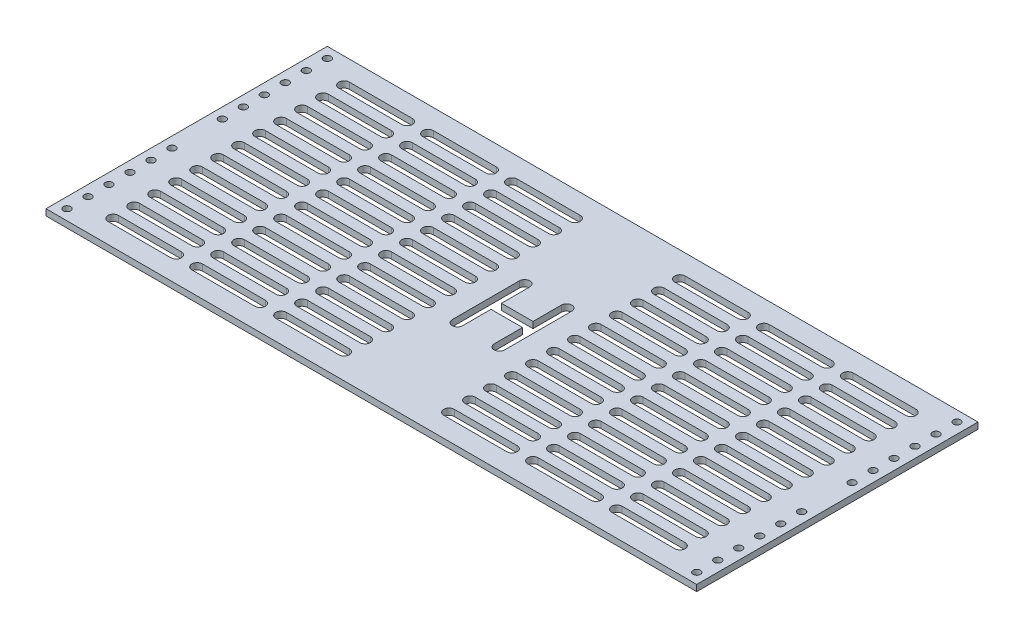
SolidWorks part; units mm, degrees
material "6061 合金"
ref_plane "前视基准面" through (0, 0, 0) normal (0, 0, 1) x (1, 0, 0)
ref_plane "上视基准面" through (0, 0, 0) normal (0, 1, 0) x (1, 0, 0)
ref_plane "右视基准面" through (0, 0, 0) normal (1, 0, 0) x (0, 0, -1)
other "Configuration Table"
sketch "草图1" plane through (0, 0, 0) normal (0, 1, 0) x (1, 0, 0)
  line L0 (0, 0) -> (-155, 0)
  line L1 (0, 0) -> (155, 0)
  line L2 (155, 0) -> (155, -134)
  line L3 (155, -134) -> (-155, -134)
  line L4 (-155, -134) -> (-155, 0)
  dimension "D1" = 155
  dimension "D2" = 134
  dimension "D3" = 155
extrude "凸台-拉伸1" add sketch "草图1" along normal blind 3
sketch "草图2" plane through (0, 3, 0) normal (0, 1, 0) x (1, 0, 0)
  line L0 (0, 0) -> (0, -134)
  line L3 (155, 0) -> (-155, 0) construction
  line L5 (-155, -134) -> (155, -134) construction
  line L6 (-155, -67) -> (155, -67)
  line L7 (-155, 0) -> (-155, -134) construction
  line L8 (155, -134) -> (155, 0) construction
  line L9 (0, -67) -> (-10, -67)
  line L10 (0, -67) -> (10, -67)
  line L11 (-10, -67) -> (-10, -51)
  line L14 (-10, -67) -> (-10, -83)
  line L17 (10, -67) -> (10, -51)
  line L22 (10, -67) -> (10, -83)
  line L23 (-10, -51) -> (-10, -83) construction
  line L24 (-7.5, -51) -> (-7.5, -83)
  line L25 (-12.5, -51) -> (-12.5, -83)
  line L26 (-10, -67) -> (10, -67) construction
  line L27 (-10, -64.5) -> (10, -64.5)
  line L28 (-10, -69.5) -> (10, -69.5)
  line L29 (10, -51) -> (10, -83) construction
  line L30 (12.5, -51) -> (12.5, -83)
  line L31 (7.5, -51) -> (7.5, -83)
  arc A6 (-7.5, -51) -> (-12.5, -51) centre (-10, -51) ccw
  arc A7 (-12.5, -83) -> (-7.5, -83) centre (-10, -83) ccw
  arc A8 (-10, -64.5) -> (-10, -69.5) centre (-10, -67) ccw
  arc A9 (10, -69.5) -> (10, -64.5) centre (10, -67) ccw
  arc A10 (12.5, -51) -> (7.5, -51) centre (10, -51) ccw
  arc A11 (7.5, -83) -> (12.5, -83) centre (10, -83) ccw
  point P15 (-10, -67)
  point P25 (0, -67)
  point P30 (10, -67)
  dimension "D1" = 10
  dimension "D2" = 10
extrude "切除-拉伸5" cut sketch "草图2" against normal blind 10
sketch "草图3" plane through (0, 3, 0) normal (0, 1, 0) x (1, 0, 0)
  line L0 (0, 0) -> (0, -134)
  line L1 (-155, -134) -> (155, -134) construction
  line L2 (-155, -67) -> (155, -67)
  line L3 (-155, 0) -> (-155, -134) construction
  line L4 (155, -134) -> (155, 0) construction
  line L5 (-155, -134) -> (-155, -122)
  line L6 (-155, -122) -> (-145, -122)
  line L7 (-145, -122) -> (-140, -122)
  line L8 (-140, -122) -> (-135, -122)
  line L9 (-135, -122) -> (-105, -122)
  line L10 (-105, -122) -> (-95, -122)
  line L11 (-95, -122) -> (-65, -122)
  line L12 (-65, -122) -> (-55, -122)
  line L13 (-55, -122) -> (-25, -122)
  line L14 (-25, -122) -> (-22, -122)
  line L18 (-135, -122) -> (-105, -122) construction
  line L19 (-135, -119.5) -> (-105, -119.5)
  line L20 (-135, -124.5) -> (-105, -124.5)
  line L21 (-95, -122) -> (-65, -122) construction
  line L22 (-95, -119.5) -> (-65, -119.5)
  line L23 (-95, -124.5) -> (-65, -124.5)
  line L24 (-55, -122) -> (-25, -122) construction
  line L25 (-55, -119.5) -> (-25, -119.5)
  line L26 (-55, -124.5) -> (-25, -124.5)
  line L37 (-135, -114.5) -> (-105, -114.5)
  line L38 (-135, -109.5) -> (-105, -109.5)
  line L47 (-95, -114.5) -> (-65, -114.5)
  line L48 (-95, -109.5) -> (-65, -109.5)
  line L49 (-55, -114.5) -> (-25, -114.5)
  line L50 (-55, -109.5) -> (-25, -109.5)
  line L60 (-135, -112) -> (-105, -112) construction
  line L61 (-95, -112) -> (-65, -112) construction
  line L62 (-55, -112) -> (-25, -112) construction
  line L73 (-135, -104.5) -> (-105, -104.5)
  line L74 (-135, -99.5) -> (-105, -99.5)
  line L83 (-95, -104.5) -> (-65, -104.5)
  line L84 (-95, -99.5) -> (-65, -99.5)
  line L85 (-55, -104.5) -> (-25, -104.5)
  line L86 (-55, -99.5) -> (-25, -99.5)
  line L96 (-135, -102) -> (-105, -102) construction
  line L97 (-95, -102) -> (-65, -102) construction
  line L98 (-55, -102) -> (-25, -102) construction
  line L109 (-135, -94.5) -> (-105, -94.5)
  line L110 (-135, -89.5) -> (-105, -89.5)
  line L119 (-95, -94.5) -> (-65, -94.5)
  line L120 (-95, -89.5) -> (-65, -89.5)
  line L121 (-55, -94.5) -> (-25, -94.5)
  line L122 (-55, -89.5) -> (-25, -89.5)
  line L132 (-135, -92) -> (-105, -92) construction
  line L133 (-95, -92) -> (-65, -92) construction
  line L134 (-55, -92) -> (-25, -92) construction
  line L145 (-135, -84.5) -> (-105, -84.5)
  line L146 (-135, -79.5) -> (-105, -79.5)
  line L155 (-95, -84.5) -> (-65, -84.5)
  line L156 (-95, -79.5) -> (-65, -79.5)
  line L157 (-55, -84.5) -> (-25, -84.5)
  line L158 (-55, -79.5) -> (-25, -79.5)
  line L168 (-135, -82) -> (-105, -82) construction
  line L169 (-95, -82) -> (-65, -82) construction
  line L170 (-55, -82) -> (-25, -82) construction
  line L181 (-135, -74.5) -> (-105, -74.5)
  line L182 (-135, -69.5) -> (-105, -69.5)
  line L191 (-95, -74.5) -> (-65, -74.5)
  line L192 (-95, -69.5) -> (-65, -69.5)
  line L193 (-55, -74.5) -> (-25, -74.5)
  line L194 (-55, -69.5) -> (-25, -69.5)
  line L204 (-135, -72) -> (-105, -72) construction
  line L205 (-95, -72) -> (-65, -72) construction
  line L206 (-55, -72) -> (-25, -72) construction
  line L367 (-135, 0.5) -> (-105, 0.5) [skipped]
  line L368 (-135, -4.5) -> (-105, -4.5) [skipped]
  line L369 (-95, 0.5) -> (-65, 0.5) [skipped]
  line L370 (-95, -4.5) -> (-65, -4.5) [skipped]
  line L371 (-55, 0.5) -> (-25, 0.5) [skipped]
  line L372 (-55, -4.5) -> (-25, -4.5) [skipped]
  line L373 (-135, 10.5) -> (-105, 10.5) [skipped]
  line L374 (-135, 5.5) -> (-105, 5.5) [skipped]
  line L375 (-95, 10.5) -> (-65, 10.5) [skipped]
  line L376 (-95, 5.5) -> (-65, 5.5) [skipped]
  line L377 (-55, 10.5) -> (-25, 10.5) [skipped]
  line L378 (-55, 5.5) -> (-25, 5.5) [skipped]
  line L379 (-135, 20.5) -> (-105, 20.5) [skipped]
  line L380 (-135, 15.5) -> (-105, 15.5) [skipped]
  line L381 (-95, 20.5) -> (-65, 20.5) [skipped]
  line L382 (-95, 15.5) -> (-65, 15.5) [skipped]
  line L383 (-55, 20.5) -> (-25, 20.5) [skipped]
  line L384 (-55, 15.5) -> (-25, 15.5) [skipped]
  line L385 (-135, 30.5) -> (-105, 30.5) [skipped]
  line L386 (-135, 25.5) -> (-105, 25.5) [skipped]
  line L387 (-95, 30.5) -> (-65, 30.5) [skipped]
  line L388 (-95, 25.5) -> (-65, 25.5) [skipped]
  line L389 (-55, 30.5) -> (-25, 30.5) [skipped]
  line L390 (-55, 25.5) -> (-25, 25.5) [skipped]
  line L391 (-135, 40.5) -> (-105, 40.5) [skipped]
  line L392 (-135, 35.5) -> (-105, 35.5) [skipped]
  line L393 (-95, 40.5) -> (-65, 40.5) [skipped]
  line L394 (-95, 35.5) -> (-65, 35.5) [skipped]
  line L395 (-55, 40.5) -> (-25, 40.5) [skipped]
  line L396 (-55, 35.5) -> (-25, 35.5) [skipped]
  line L397 (-135, 50.5) -> (-105, 50.5) [skipped]
  line L398 (-135, 45.5) -> (-105, 45.5) [skipped]
  line L399 (-95, 50.5) -> (-65, 50.5) [skipped]
  line L400 (-95, 45.5) -> (-65, 45.5) [skipped]
  line L401 (-55, 50.5) -> (-25, 50.5) [skipped]
  line L402 (-55, 45.5) -> (-25, 45.5) [skipped]
  line L403 (-135, -59.5) -> (-105, -59.5) [skipped]
  line L404 (-135, -64.5) -> (-105, -64.5) [skipped]
  line L405 (-95, -59.5) -> (-65, -59.5) [skipped]
  line L406 (-95, -64.5) -> (-65, -64.5) [skipped]
  line L407 (-55, -59.5) -> (-25, -59.5) [skipped]
  line L408 (-55, -64.5) -> (-25, -64.5) [skipped]
  line L409 (-135, -49.5) -> (-105, -49.5) [skipped]
  line L410 (-135, -54.5) -> (-105, -54.5) [skipped]
  line L411 (-95, -49.5) -> (-65, -49.5) [skipped]
  line L412 (-95, -54.5) -> (-65, -54.5) [skipped]
  line L413 (-55, -49.5) -> (-25, -49.5) [skipped]
  line L414 (-55, -54.5) -> (-25, -54.5) [skipped]
  line L415 (-135, -39.5) -> (-105, -39.5) [skipped]
  line L416 (-135, -44.5) -> (-105, -44.5) [skipped]
  line L417 (-95, -39.5) -> (-65, -39.5) [skipped]
  line L418 (-95, -44.5) -> (-65, -44.5) [skipped]
  line L419 (-55, -39.5) -> (-25, -39.5) [skipped]
  line L420 (-55, -44.5) -> (-25, -44.5) [skipped]
  line L421 (-135, -29.5) -> (-105, -29.5) [skipped]
  line L422 (-135, -34.5) -> (-105, -34.5) [skipped]
  line L423 (-95, -29.5) -> (-65, -29.5) [skipped]
  line L424 (-95, -34.5) -> (-65, -34.5) [skipped]
  line L425 (-55, -29.5) -> (-25, -29.5) [skipped]
  line L426 (-55, -34.5) -> (-25, -34.5) [skipped]
  line L427 (-135, -19.5) -> (-105, -19.5) [skipped]
  line L428 (-135, -24.5) -> (-105, -24.5) [skipped]
  line L429 (-95, -19.5) -> (-65, -19.5) [skipped]
  line L430 (-95, -24.5) -> (-65, -24.5) [skipped]
  line L431 (-55, -19.5) -> (-25, -19.5) [skipped]
  line L432 (-55, -24.5) -> (-25, -24.5) [skipped]
  line L433 (-135, -9.5) -> (-105, -9.5) [skipped]
  line L434 (-135, -14.5) -> (-105, -14.5) [skipped]
  line L435 (-95, -9.5) -> (-65, -9.5) [skipped]
  line L436 (-95, -14.5) -> (-65, -14.5) [skipped]
  line L437 (-55, -9.5) -> (-25, -9.5) [skipped]
  line L438 (-55, -14.5) -> (-25, -14.5) [skipped]
  arc A2 (-135, -119.5) -> (-135, -124.5) centre (-135, -122) ccw
  arc A3 (-105, -124.5) -> (-105, -119.5) centre (-105, -122) ccw
  arc A4 (-95, -119.5) -> (-95, -124.5) centre (-95, -122) ccw
  arc A5 (-65, -124.5) -> (-65, -119.5) centre (-65, -122) ccw
  arc A6 (-55, -119.5) -> (-55, -124.5) centre (-55, -122) ccw
  arc A7 (-25, -124.5) -> (-25, -119.5) centre (-25, -122) ccw
  arc A146 (-135, -109.5) -> (-135, -114.5) centre (-135, -112) ccw
  arc A147 (-105, -114.5) -> (-105, -109.5) centre (-105, -112) ccw
  arc A148 (-95, -109.5) -> (-95, -114.5) centre (-95, -112) ccw
  arc A149 (-65, -114.5) -> (-65, -109.5) centre (-65, -112) ccw
  arc A150 (-55, -109.5) -> (-55, -114.5) centre (-55, -112) ccw
  arc A151 (-25, -114.5) -> (-25, -109.5) centre (-25, -112) ccw
  arc A154 (-135, -99.5) -> (-135, -104.5) centre (-135, -102) ccw
  arc A155 (-105, -104.5) -> (-105, -99.5) centre (-105, -102) ccw
  arc A156 (-95, -99.5) -> (-95, -104.5) centre (-95, -102) ccw
  arc A157 (-65, -104.5) -> (-65, -99.5) centre (-65, -102) ccw
  arc A158 (-55, -99.5) -> (-55, -104.5) centre (-55, -102) ccw
  arc A159 (-25, -104.5) -> (-25, -99.5) centre (-25, -102) ccw
  arc A162 (-135, -89.5) -> (-135, -94.5) centre (-135, -92) ccw
  arc A163 (-105, -94.5) -> (-105, -89.5) centre (-105, -92) ccw
  arc A164 (-95, -89.5) -> (-95, -94.5) centre (-95, -92) ccw
  arc A165 (-65, -94.5) -> (-65, -89.5) centre (-65, -92) ccw
  arc A166 (-55, -89.5) -> (-55, -94.5) centre (-55, -92) ccw
  arc A167 (-25, -94.5) -> (-25, -89.5) centre (-25, -92) ccw
  arc A170 (-135, -79.5) -> (-135, -84.5) centre (-135, -82) ccw
  arc A171 (-105, -84.5) -> (-105, -79.5) centre (-105, -82) ccw
  arc A172 (-95, -79.5) -> (-95, -84.5) centre (-95, -82) ccw
  arc A173 (-65, -84.5) -> (-65, -79.5) centre (-65, -82) ccw
  arc A174 (-55, -79.5) -> (-55, -84.5) centre (-55, -82) ccw
  arc A175 (-25, -84.5) -> (-25, -79.5) centre (-25, -82) ccw
  arc A178 (-135, -69.5) -> (-135, -74.5) centre (-135, -72) ccw
  arc A179 (-105, -74.5) -> (-105, -69.5) centre (-105, -72) ccw
  arc A180 (-95, -69.5) -> (-95, -74.5) centre (-95, -72) ccw
  arc A181 (-65, -74.5) -> (-65, -69.5) centre (-65, -72) ccw
  arc A182 (-55, -69.5) -> (-55, -74.5) centre (-55, -72) ccw
  arc A183 (-25, -74.5) -> (-25, -69.5) centre (-25, -72) ccw
  arc A280 (-135, 0.5) -> (-135, -4.5) centre (-135, -2) ccw [skipped]
  arc A281 (-105, -4.5) -> (-105, 0.5) centre (-105, -2) ccw [skipped]
  arc A282 (-95, 0.5) -> (-95, -4.5) centre (-95, -2) ccw [skipped]
  arc A283 (-65, -4.5) -> (-65, 0.5) centre (-65, -2) ccw [skipped]
  arc A284 (-55, 0.5) -> (-55, -4.5) centre (-55, -2) ccw [skipped]
  arc A285 (-25, -4.5) -> (-25, 0.5) centre (-25, -2) ccw [skipped]
  arc A286 (-135, 10.5) -> (-135, 5.5) centre (-135, 8) ccw [skipped]
  arc A287 (-105, 5.5) -> (-105, 10.5) centre (-105, 8) ccw [skipped]
  arc A288 (-95, 10.5) -> (-95, 5.5) centre (-95, 8) ccw [skipped]
  arc A289 (-65, 5.5) -> (-65, 10.5) centre (-65, 8) ccw [skipped]
  arc A290 (-55, 10.5) -> (-55, 5.5) centre (-55, 8) ccw [skipped]
  arc A291 (-25, 5.5) -> (-25, 10.5) centre (-25, 8) ccw [skipped]
  arc A292 (-135, 20.5) -> (-135, 15.5) centre (-135, 18) ccw [skipped]
  arc A293 (-105, 15.5) -> (-105, 20.5) centre (-105, 18) ccw [skipped]
  arc A294 (-95, 20.5) -> (-95, 15.5) centre (-95, 18) ccw [skipped]
  arc A295 (-65, 15.5) -> (-65, 20.5) centre (-65, 18) ccw [skipped]
  arc A296 (-55, 20.5) -> (-55, 15.5) centre (-55, 18) ccw [skipped]
  arc A297 (-25, 15.5) -> (-25, 20.5) centre (-25, 18) ccw [skipped]
  arc A298 (-135, 30.5) -> (-135, 25.5) centre (-135, 28) ccw [skipped]
  arc A299 (-105, 25.5) -> (-105, 30.5) centre (-105, 28) ccw [skipped]
  arc A300 (-95, 30.5) -> (-95, 25.5) centre (-95, 28) ccw [skipped]
  arc A301 (-65, 25.5) -> (-65, 30.5) centre (-65, 28) ccw [skipped]
  arc A302 (-55, 30.5) -> (-55, 25.5) centre (-55, 28) ccw [skipped]
  arc A303 (-25, 25.5) -> (-25, 30.5) centre (-25, 28) ccw [skipped]
  arc A304 (-135, 40.5) -> (-135, 35.5) centre (-135, 38) ccw [skipped]
  arc A305 (-105, 35.5) -> (-105, 40.5) centre (-105, 38) ccw [skipped]
  arc A306 (-95, 40.5) -> (-95, 35.5) centre (-95, 38) ccw [skipped]
  arc A307 (-65, 35.5) -> (-65, 40.5) centre (-65, 38) ccw [skipped]
  arc A308 (-55, 40.5) -> (-55, 35.5) centre (-55, 38) ccw [skipped]
  arc A309 (-25, 35.5) -> (-25, 40.5) centre (-25, 38) ccw [skipped]
  arc A310 (-135, 50.5) -> (-135, 45.5) centre (-135, 48) ccw [skipped]
  arc A311 (-105, 45.5) -> (-105, 50.5) centre (-105, 48) ccw [skipped]
  arc A312 (-95, 50.5) -> (-95, 45.5) centre (-95, 48) ccw [skipped]
  arc A313 (-65, 45.5) -> (-65, 50.5) centre (-65, 48) ccw [skipped]
  arc A314 (-55, 50.5) -> (-55, 45.5) centre (-55, 48) ccw [skipped]
  arc A315 (-25, 45.5) -> (-25, 50.5) centre (-25, 48) ccw [skipped]
  arc A316 (-135, -59.5) -> (-135, -64.5) centre (-135, -62) ccw [skipped]
  arc A317 (-105, -64.5) -> (-105, -59.5) centre (-105, -62) ccw [skipped]
  arc A318 (-95, -59.5) -> (-95, -64.5) centre (-95, -62) ccw [skipped]
  arc A319 (-65, -64.5) -> (-65, -59.5) centre (-65, -62) ccw [skipped]
  arc A320 (-55, -59.5) -> (-55, -64.5) centre (-55, -62) ccw [skipped]
  arc A321 (-25, -64.5) -> (-25, -59.5) centre (-25, -62) ccw [skipped]
  arc A322 (-135, -49.5) -> (-135, -54.5) centre (-135, -52) ccw [skipped]
  arc A323 (-105, -54.5) -> (-105, -49.5) centre (-105, -52) ccw [skipped]
  arc A324 (-95, -49.5) -> (-95, -54.5) centre (-95, -52) ccw [skipped]
  arc A325 (-65, -54.5) -> (-65, -49.5) centre (-65, -52) ccw [skipped]
  arc A326 (-55, -49.5) -> (-55, -54.5) centre (-55, -52) ccw [skipped]
  arc A327 (-25, -54.5) -> (-25, -49.5) centre (-25, -52) ccw [skipped]
  arc A328 (-135, -39.5) -> (-135, -44.5) centre (-135, -42) ccw [skipped]
  arc A329 (-105, -44.5) -> (-105, -39.5) centre (-105, -42) ccw [skipped]
  arc A330 (-95, -39.5) -> (-95, -44.5) centre (-95, -42) ccw [skipped]
  arc A331 (-65, -44.5) -> (-65, -39.5) centre (-65, -42) ccw [skipped]
  arc A332 (-55, -39.5) -> (-55, -44.5) centre (-55, -42) ccw [skipped]
  arc A333 (-25, -44.5) -> (-25, -39.5) centre (-25, -42) ccw [skipped]
  arc A334 (-135, -29.5) -> (-135, -34.5) centre (-135, -32) ccw [skipped]
  arc A335 (-105, -34.5) -> (-105, -29.5) centre (-105, -32) ccw [skipped]
  arc A336 (-95, -29.5) -> (-95, -34.5) centre (-95, -32) ccw [skipped]
  arc A337 (-65, -34.5) -> (-65, -29.5) centre (-65, -32) ccw [skipped]
  arc A338 (-55, -29.5) -> (-55, -34.5) centre (-55, -32) ccw [skipped]
  arc A339 (-25, -34.5) -> (-25, -29.5) centre (-25, -32) ccw [skipped]
  arc A340 (-135, -19.5) -> (-135, -24.5) centre (-135, -22) ccw [skipped]
  arc A341 (-105, -24.5) -> (-105, -19.5) centre (-105, -22) ccw [skipped]
  arc A342 (-95, -19.5) -> (-95, -24.5) centre (-95, -22) ccw [skipped]
  arc A343 (-65, -24.5) -> (-65, -19.5) centre (-65, -22) ccw [skipped]
  arc A344 (-55, -19.5) -> (-55, -24.5) centre (-55, -22) ccw [skipped]
  arc A345 (-25, -24.5) -> (-25, -19.5) centre (-25, -22) ccw [skipped]
  arc A346 (-135, -9.5) -> (-135, -14.5) centre (-135, -12) ccw [skipped]
  arc A347 (-105, -14.5) -> (-105, -9.5) centre (-105, -12) ccw [skipped]
  arc A348 (-95, -9.5) -> (-95, -14.5) centre (-95, -12) ccw [skipped]
  arc A349 (-65, -14.5) -> (-65, -9.5) centre (-65, -12) ccw [skipped]
  arc A350 (-55, -9.5) -> (-55, -14.5) centre (-55, -12) ccw [skipped]
  arc A351 (-25, -14.5) -> (-25, -9.5) centre (-25, -12) ccw [skipped]
  point P28 (-120, -122)
  point P33 (-80, -122)
  point P38 (-40, -122)
  point P58 (-120, -112)
  point P63 (-80, -112)
  point P68 (-40, -112)
  point P86 (-120, -102)
  point P91 (-80, -102)
  point P96 (-40, -102)
  point P114 (-120, -92)
  point P119 (-80, -92)
  point P124 (-40, -92)
  point P142 (-120, -82)
  point P147 (-80, -82)
  point P152 (-40, -82)
  point P170 (-120, -72)
  point P175 (-80, -72)
  point P180 (-40, -72)
  dimension "D1" = 12
  dimension "D3" = 18
  dimension "D2" = 10
  dimension "D4" = 5
  dimension "D5" = 5
  dimension "D6" = 30
  dimension "D7" = 10
  dimension "D8" = 30
  dimension "D9" = 10
  dimension "D10" = 30
extrude "切除-拉伸2" cut sketch "草图3" against normal through all
ref_plane "基准面1" through (0, 0, 67) normal (0, 0, 1) x (1, 0, 0)
mirror "镜向1" about plane through (0, 0, 67) normal (0, 0, 1) of "切除-拉伸2"
mirror "镜向2" about plane through (0, 0, 0) normal (1, 0, 0) of "镜向1", "切除-拉伸2"
sketch "草图4" plane through (0, 3, 0) normal (0, 1, 0) x (1, 0, 0)
  line L0 (-155, -134) -> (-150, -134)
  line L1 (-155, -134) -> (155, -134) construction
  line L2 (-150, -134) -> (-150, -129)
  circle A0 centre (-150, -129) radius 1.75
  circle A1 centre (-150, -119) radius 1.75
  circle A2 centre (-150, -109) radius 1.75
  circle A3 centre (-150, -99) radius 1.75
  circle A4 centre (-150, -89) radius 1.75
  circle A5 centre (-150, -79) radius 1.75
  circle A19 centre (-150, -49) radius 1.75 [skipped]
  circle A20 centre (-150, -39) radius 1.75 [skipped]
  circle A21 centre (-150, -29) radius 1.75 [skipped]
  circle A22 centre (-150, -19) radius 1.75 [skipped]
  circle A23 centre (-150, -9) radius 1.75 [skipped]
  circle A24 centre (-150, 1) radius 1.75 [skipped]
  circle A25 centre (-150, 11) radius 1.75 [skipped]
  circle A26 centre (-150, 21) radius 1.75 [skipped]
  circle A27 centre (-150, 31) radius 1.75 [skipped]
  circle A28 centre (-150, 41) radius 1.75 [skipped]
  circle A29 centre (-150, 51) radius 1.75 [skipped]
  circle A30 centre (-150, -69) radius 1.75 [skipped]
  circle A31 centre (-150, -59) radius 1.75 [skipped]
  dimension "D3" = 19
  dimension "D1" = 5
  dimension "D2" = 5
extrude "切除-拉伸3" cut sketch "草图4" against normal through all
mirror "镜向3" about plane through (0, 0, 67) normal (0, 0, 1) of "切除-拉伸3"
mirror "镜向4" about plane through (0, 0, 0) normal (1, 0, 0) of "镜向3", "切除-拉伸3"
